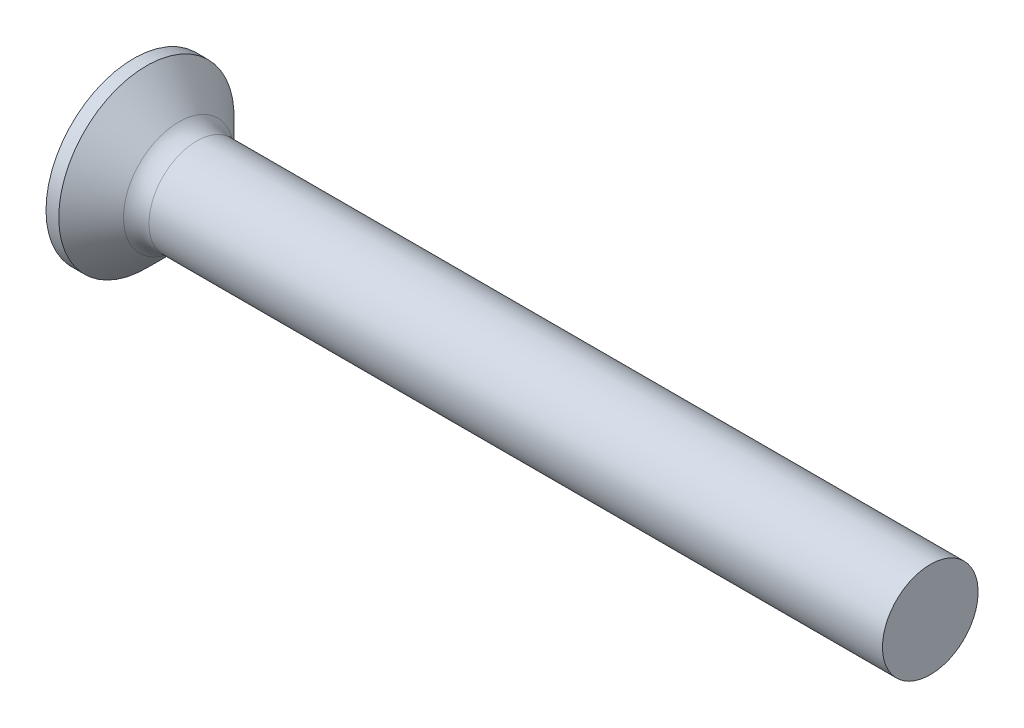
SolidWorks part; units mm, degrees
revolve "Base-Revolve" add sketch "BodySke"
sketch "BodySke" plane through (0, 0, 0) normal (0, 0, 1) x (1, 0, 0)
  line L0 (0, 0) -> (0, 2.75)
  line L1 (0, 2.75) -> (0.4, 2.75)
  line L2 (1.65, 1.5) -> (25, 1.5)
  line L3 (25, 1.5) -> (25, 0)
  line L4 (25, 0) -> (0, 0)
  line L5 (-6.35, 0) -> (82.55, 0) construction
  line L6 (1.65, -1.5) -> (25, -1.5) construction
  line L7 (0.4, -2.75) -> (1.65, -1.5) construction
  line L8 (0.4, 2.75) -> (1.65, 1.5)
  line L9 (0, -2.75) -> (0.4, -2.75) construction
  line L10 (2.15, 3.0875) -> (2.15, -6.4375) construction
  line L11 (0, 6.35) -> (0, -3.175) construction
  dimension "Diameter" = 3
  dimension "Head_ht" = 1.65
  dimension "Head_dia" = 5.5
  dimension "Head_ang" = 90
  dimension "D6" = 0.4
  dimension "Advance" = 0.5
cosmetic thread "ThreadCosmetic" [suppressed]
fillet "Fillet1" radius 0.8 1 edges at (1.65, 0, 1.5)
ref_plane "Plane1" through (0, 0, 0) normal (0, 0, 1) x (1, 0, 0)
ref_plane "Plane2" through (0, 0, 0) normal (0, 1, 0) x (1, 0, 0)
ref_plane "Plane3" through (0, 0, 0) normal (1, 0, 0) x (0, 0, -1)
sketch "Sketch3" plane through (0, 0, 0) normal (-1, 0, 0) x (0, 0, 1)
  line L0 (-0.37, 1.5) -> (0.37, 1.5)
  line L1 (0.37, 1.5) -> (0.37, -1.5)
  line L2 (0.37, -1.5) -> (-0.37, -1.5)
  line L3 (-0.37, -1.5) -> (-0.37, 1.5)
  dimension "Cross_dia" = 3
  dimension "Cross_width" = 0.74
  dimension "D1" = 1.5
  dimension "D2" = 0.37
ref_plane "Plane4" through (2.01, 0, 0) normal (-1, 0, 0) x (0, 0, 1)
sketch "Sketch4" plane through (2.01, 0, 0) normal (-1, 0, 0) x (0, 0, 1)
  line L0 (-0.37, 0.4979) -> (0.37, 0.4979)
  line L3 (0.37, 0.4979) -> (0.37, -0.4979)
  line L4 (0.37, -0.4979) -> (-0.37, -0.4979)
  line L5 (-0.37, -0.4979) -> (-0.37, 0.4979)
  dimension "D2" = 0.9957
  dimension "D1" = 0.74
  dimension "D4" = 0.4979
  dimension "D3" = 0.37
loft "Recess" cut profiles "Sketch3", "Sketch4"
pattern_circular "RecPat" count 2 every 90 about axis through (0, 0, 0) along (1, 0, 0) of "Recess"
sketch "RecCorSke" plane through (0, 0, 0) normal (0, 0, 1) x (1, 0, 0)
  line L0 (-3.175, 0) -> (15.875, 0) construction
  line L2 (0, 0) -> (0, 0.6966)
  line L3 (0, 0.6966) -> (2.01, 0.556)
  line L4 (2.01, 0.556) -> (2.1907, 0)
  line L5 (2.1907, 0) -> (0, 0)
  dimension "Diameter" = 1.112
  dimension "Depth" = 2.01
  dimension "Draft_angle" = 4
  dimension "Bottom_angle" = 18
revolve "RecessCore" cut sketch "RecCorSke" angle 360 about L0
sketch "ThdSchSke" plane through (0, 0, 0) normal (0, 0, 1) x (1, 0, 0)
  line L0 (2.15, -1.2195) -> (1.9536, -1.5)
  line L1 (2.15, -1.2195) -> (2.3464, -1.5)
  line L2 (2.3464, -1.5) -> (2.3464, -1.875)
  line L3 (-3.175, 0) -> (5.1513, 0) construction
  line L5 (2.3464, -1.875) -> (1.9536, -1.875)
  line L6 (1.9536, -1.875) -> (1.9536, -1.5)
  line L7 (0, 2.75) -> (0, -2.75) construction
  dimension "Diameter" = 3
  dimension "Thread_minor" = 2.439
  dimension "Start" = 2.15
revolve "ThreadSchematic" [suppressed] cut sketch "ThdSchSke" angle 360 about L3
pattern_linear "ThdSchPat" [suppressed]
equation "\"D1@Sketch3\" = \"Cross_dia@Sketch3\" / 2"
equation "\"D2@Sketch3\" = \"Cross_width@Sketch3\" / 2"
equation "\"Depth@RecCorSke\" = \"Cross_depth@Plane4\""
equation "\"D1@Sketch4\" = \"Cross_width@Sketch3\""
equation "\"D2@Sketch4\" = \"Cross_dia@Sketch3\" - 2.0 * \"Cross_depth@Plane4\" * tan(26.5  * 0.017453292)"
equation "\"D3@Sketch4\" = \"D1@Sketch4\" / 2"
equation "\"D4@Sketch4\" = \"D2@Sketch4\" / 2"
equation "\"Thread_length@ThreadCosmetic\" = ((sgn( (\"Length@BodySke\" - \"Advance@BodySke\" * 1.0 - \"Head_ht@BodySke\" ) - \"Thread_nom@BodySke\" )-1)*( (\"Length@BodySke\" - \"Advance@BodySke\" * 1.0 - \"Head_ht@BodySke\" ) - \"Thread_nom@BodySke\" ))/-2+ \"Thread_nom@BodySke\""
equation "\"Thread_minor@ThdSchSke\" = \"Thread_minor@ThreadCosmetic\""
equation "\"Diameter@ThdSchSke\" = \"Diameter@BodySke\""
equation "\"Overcut@ThdSchSke\" = \"Diameter@BodySke\" * 1.25"
equation "\"Start@ThdSchSke\" = 0.000001 + \"Length@BodySke\" - \"Thread_length@ThreadCosmetic\"  '---Countersunk---"
equation "\"Num_threads@ThdSchPat\" = int( \"Thread_length@ThreadCosmetic\" / \"Advance@BodySke\" + 0.999 )  + 1"
equation "\"Advance@ThdSchPat\" = \"Thread_length@ThreadCosmetic\" /  (\"Num_threads@ThdSchPat\" - 1) 'relax it"
